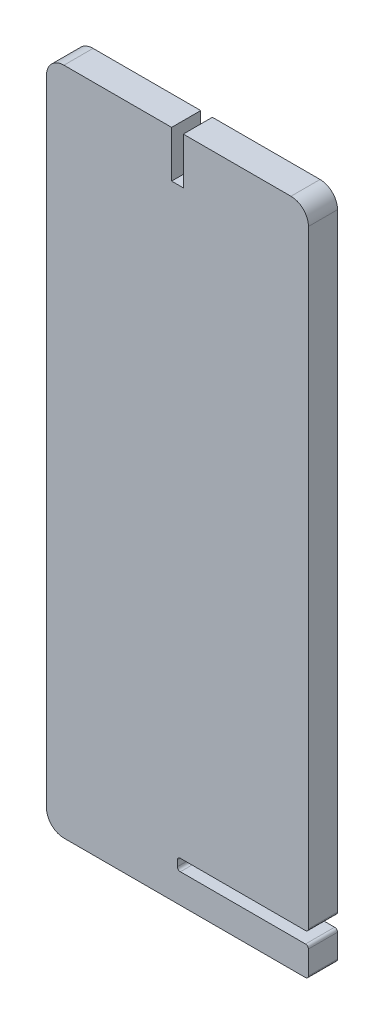
SolidWorks part; units mm, degrees
ref_plane "Alzado" through (0, 0, 0) normal (0, 0, 1) x (1, 0, 0)
ref_plane "Planta" through (0, 0, 0) normal (0, 1, 0) x (1, 0, 0)
ref_plane "Vista lateral" through (0, 0, 0) normal (1, 0, 0) x (0, 0, -1)
sketch "Croquis1" plane through (0, 0, 0) normal (0, 0, 1) x (1, 0, 0)
  line L1 (-22.5, 45) -> (22.5, 45)
  line L2 (-22.5, 45) -> (-22.5, -70)
  line L3 (-22.5, -70) -> (22.5, -70)
  line L4 (22.5, 45) -> (22.5, -70)
  dimension "D1" = 45
  dimension "D2" = 22.5
  dimension "D3" = 115
  dimension "D4" = 45
extrude "Saliente-Extruir1" add sketch "Croquis1" along normal blind 5 contours L2 L3 L4 L1
sketch "Croquis3" plane through (0, 0, 5) normal (0, 0, 1) x (1, 0, 0)
  line L0 (22.5, 45) -> (22.5, -70) construction
  line L1 (22.5, -63) -> (0, -63)
  line L2 (22.5, -63) -> (22.5, -65)
  line L3 (22.5, -65) -> (0, -65)
  line L4 (0, -63) -> (0, -65)
  line L5 (-22.5, -70) -> (22.5, -70) construction
  dimension "D1" = 2
  dimension "D2" = 5
  dimension "D3" = 22.5
extrude "Cortar-Extruir2" cut sketch "Croquis3" against normal up to surface (5 mm away) up to face at (0, -12.5, 0)
fillet "Redondeo1" radius 3 3 edges at (-22.5, -70, 2.5) (22.5, 45, 2.5) (-22.5, 45, 2.5)
sketch "Croquis4" plane through (0, 0, 5) normal (0, 0, 1) x (1, 0, 0)
  line L5 (0, 0) -> (0, 53.685) construction
  line L6 (-19.5, 45) -> (19.5, 45) construction
  line L7 (-1, 45) -> (1, 45)
  line L8 (-1, 45) -> (-1, 37)
  line L9 (-1, 37) -> (1, 37)
  line L10 (1, 45) -> (1, 37)
  dimension "D1" = 1
  dimension "D2" = 1
  dimension "D3" = 8
extrude "Cortar-Extruir3" cut sketch "Croquis4" against normal up to surface (5 mm away) up to face at (2.2617, -26.2162, 0)
fillet "Redondeo2" radius 0.5 5 edges at (0, -63, 2.5) (0, -65, 2.5) (22.5, -70, 2.5) (22.5, -65, 2.5) (22.5, -63, 2.5)
